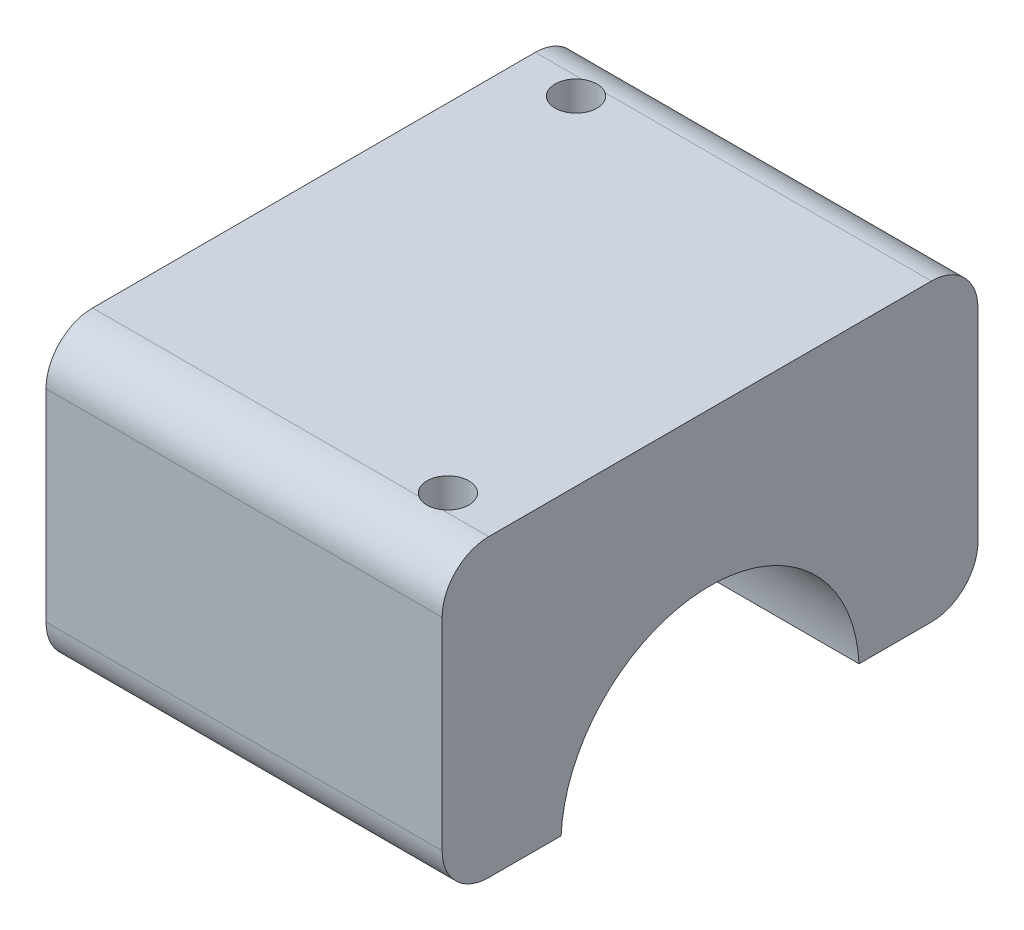
SolidWorks part; units mm, degrees
ref_plane "Front Plane" through (0, 0, 0) normal (0, 0, 1) x (1, 0, 0)
ref_plane "Top Plane" through (0, 0, 0) normal (0, 1, 0) x (1, 0, 0)
ref_plane "Right Plane" through (0, 0, 0) normal (1, 0, 0) x (0, 0, -1)
sketch "Sketch1" plane through (0, 0, 0) normal (1, 0, 0) x (0, 0, -1)
  line L0 (-19, 0.6) -> (19, 0.6)
  line L1 (23, 4.6) -> (23, 21.951)
  line L2 (19, 25.951) -> (-19, 25.951)
  line L3 (-23, 21.951) -> (-23, 4.6)
  arc A0 (19, 0.6) -> (23, 4.6) centre (19, 4.6) ccw
  arc A1 (23, 21.951) -> (19, 25.951) centre (19, 21.951) ccw
  arc A2 (-19, 25.951) -> (-23, 21.951) centre (-19, 21.951) ccw
  arc A3 (-23, 4.6) -> (-19, 0.6) centre (-19, 4.6) ccw
extrude "Boss-Extrude1" add sketch "Sketch1" along normal mid plane 34
sketch "Sketch2" plane through (0, 0, 0) normal (1, 0, 0) x (0, 0, -1)
  circle A0 centre (0, 0) radius 12.8
extrude "Cut-Extrude1" cut sketch "Sketch2" against normal through all and the other way through all
ref_plane "Plane1" through (0, 0.6, 0) normal (0, 1, 0) x (1, 0, 0)
sketch "Sketch3" plane through (0, 0.6, 0) normal (0, 1, 0) x (1, 0, 0)
  circle A0 centre (12, -17.5) radius 1.8
  circle A1 centre (-12, 17.5) radius 1.8
extrude "Cut-Extrude2" cut sketch "Sketch3" along normal blind 25.951
